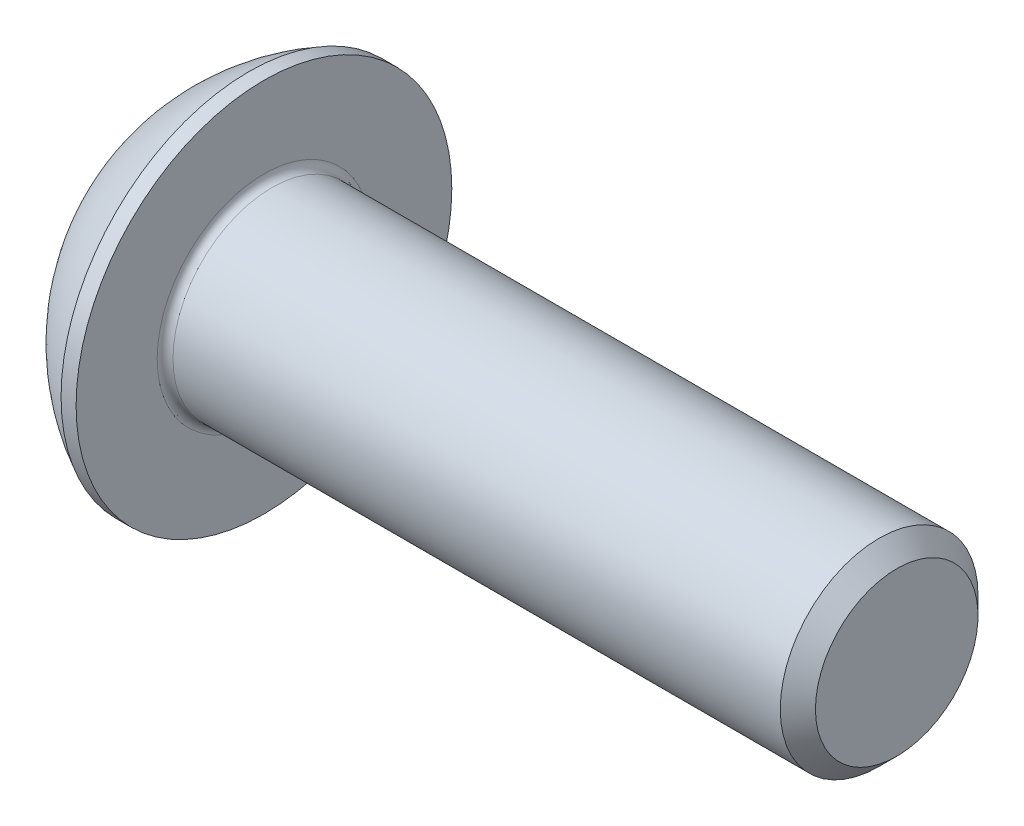
SolidWorks part; units mm, degrees
ref_plane "Plane1" through (0, 0, 0) normal (0, 0, 1) x (1, 0, 0)
ref_plane "Plane2" through (0, 0, 0) normal (0, 1, 0) x (1, 0, 0)
ref_plane "Plane3" through (0, 0, 0) normal (1, 0, 0) x (0, 0, -1)
sketch "BodySke" plane through (0, 0, 0) normal (0, 0, 1) x (1, 0, 0)
  line L0 (18.75, 0) -> (18.75, 2.055)
  line L1 (18.305, 2.5) -> (2.75, 2.5)
  line L2 (2.75, 2.5) -> (2.75, 4.75)
  line L3 (2.75, 4.75) -> (2.37, 4.75)
  line L4 (0, 0) -> (101.6, 0) construction
  line L5 (2.75, -4.75) -> (2.37, -4.75) construction
  line L6 (55.6768, -2.5) -> (2.75, -2.5) construction
  line L7 (18.75, 0) -> (0, 0)
  line L8 (0, 2.375) -> (0, -2.375) construction
  line L9 (0, 0) -> (0, 2.375)
  line L10 (18.75, 2.055) -> (18.305, 2.5)
  line L11 (18.75, -2.055) -> (18.305, -2.5) construction
  line L12 (3.55, 9.525) -> (3.55, -2.5) construction
  line L13 (2.75, 9.525) -> (2.75, -2.5) construction
  arc A1 (0, 2.375) -> (2.37, 4.75) centre (4.755, 0) cw
  dimension "D1" = 4.75
  dimension "Diameter" = 5
  dimension "Length" = 16
  dimension "Head_dia" = 9.5
  dimension "Head_ht" = 2.75
  dimension "Head_side_ht" = 0.38
  dimension "Minor_dia" = 4.11
  dimension "Body_ch_ang" = 45
  dimension "Advance" = 0.8
  dimension "Thread_nom" = 16
revolve "BaseBody" add sketch "BodySke" angle 360 about L4
cosmetic thread "ThreadCosmetic" [suppressed] parameters "Thread_length"=14.4, "Thread_minor"=4.11
fillet "Fillet1" radius 0.2 1 edges at (2.75, 0, 2.5)
sketch "Sketch2" plane through (0, 0, 0) normal (0, 0, 1) x (1, 0, 0)
  line L0 (0, 1.5) -> (1.56, 1.5)
  line L1 (1.56, 1.5) -> (2.426, 0)
  line L3 (2.426, 0) -> (0, 0)
  line L4 (0, 0) -> (0, 1.5)
  line L5 (0, -1.5) -> (1.56, -1.5) construction
  line L6 (0, 0) -> (47.625, 0) construction
  dimension "D2" = 60
  dimension "PreBroach_depth" = 1.56
  dimension "PreBroach_dia" = 3
revolve "PreBroach" cut sketch "Sketch2" angle 360 about L6
sketch "Sketch3" plane through (0, 0, 0) normal (1, 0, 0) x (0, 0, -1)
  line L0 (-1.5, -0.866) -> (-1.5, 0.866)
  line L1 (-1.5, 0.866) -> (0, 1.7321)
  line L2 (0, 1.7321) -> (1.5, 0.866)
  line L3 (1.5, 0.866) -> (1.5, -0.866)
  line L4 (1.5, -0.866) -> (0, -1.7321)
  line L5 (0, -1.7321) -> (-1.5, -0.866)
  dimension "D1" = 1.5
  dimension "D2" = 1.5
  dimension "D3" = 3
  dimension "Hex_size" = 3
extrude "Hex" cut sketch "Sketch3" along normal blind 1.56
sketch "ThdSchSke" plane through (0, 0, 0) normal (0, 0, 1) x (1, 0, 0)
  line L0 (4.35, -2.055) -> (4.0384, -2.5)
  line L1 (4.35, -2.055) -> (4.6616, -2.5)
  line L2 (4.6616, -2.5) -> (4.6616, -3.125)
  line L3 (-3.175, 0) -> (5.1513, 0) construction
  line L5 (4.6616, -3.125) -> (4.0384, -3.125)
  line L6 (4.0384, -3.125) -> (4.0384, -2.5)
  dimension "Thread_minor" = 4.11
  dimension "Diameter" = 5
  dimension "Start" = 4.35
  dimension "SideAngle" = 55
  dimension "VeeAngle" = 70
  dimension "Overcut" = 6.25
revolve "ThreadSchematic" [suppressed] cut sketch "ThdSchSke" angle 360 about L3
pattern_linear "ThdSchPat" [suppressed]
equation "\"D1@BodySke\" = \"Head_dia@BodySke\" * .5"
equation "\"Thread_minor@ThreadCosmetic\" = \"Minor_dia@BodySke\""
equation "\"D1@Sketch3\" = \"Hex_size@Sketch3\" / 2"
equation "\"D2@Sketch3\" = \"D1@Sketch3\""
equation "\"D3@Sketch3\" = \"Hex_size@Sketch3\""
equation "\"Thread_length@ThreadCosmetic\" = ((sgn( (\"Length@BodySke\" - \"Advance@BodySke\" * 2.0) - \"Thread_nom@BodySke\" )-1)*( (\"Length@BodySke\" - \"Advance@BodySke\" * 2.0) - \"Thread_nom@BodySke\" ))/-2+ \"Thread_nom@BodySke\""
equation "\"Thread_minor@ThdSchSke\" = \"Minor_dia@BodySke\""
equation "\"Diameter@ThdSchSke\" = \"Diameter@BodySke\""
equation "\"Overcut@ThdSchSke\" = \"Diameter@BodySke\" * 1.25"
equation "\"Start@ThdSchSke\" = \"Head_ht@BodySke\" + \"Length@BodySke\" - \"Thread_length@ThreadCosmetic\"  '---Non-countersunk---"
equation "\"Num_threads@ThdSchPat\" = int( \"Thread_length@ThreadCosmetic\" / \"Advance@BodySke\" + 0.999 )  + 1"
equation "\"Advance@ThdSchPat\" = \"Thread_length@ThreadCosmetic\" /  (\"Num_threads@ThdSchPat\" - 1) 'relax it"
equation "\"Num_threads@ThdSchPat\" = \"Num_threads@ThdSchPat\" - sgn( \"Num_threads@ThdSchPat\" - 1) '---chamfered tips only---"
